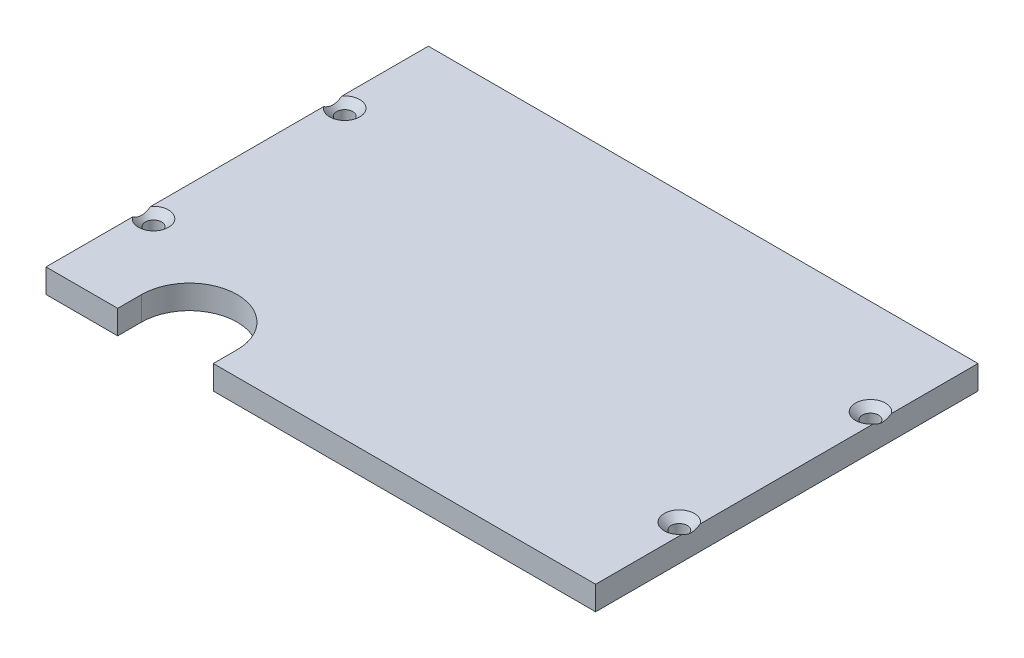
SolidWorks part; units mm, degrees
material "Acrylic"
ref_plane "Front" through (0, 0, 0) normal (0, 0, 1) x (1, 0, 0)
ref_plane "Top" through (0, 0, 0) normal (0, 1, 0) x (1, 0, 0)
ref_plane "Right" through (0, 0, 0) normal (1, 0, 0) x (0, 0, -1)
sketch "Sketch1" plane through (0, 0, 0) normal (0, 1, 0) x (1, 0, 0)
  line L0 (15, 5) -> (15, 0)
  line L1 (0, 0) -> (15, 0)
  line L2 (0, 0) -> (0, 80)
  line L3 (0, 80) -> (115, 80)
  line L4 (115, 0) -> (115, 80)
  line L5 (35, 5) -> (35, 0)
  line L6 (35, 0) -> (115, 0)
  arc A0 (35, 5) -> (15, 5) centre (25, 5) ccw
  dimension "D4" = 10
  dimension "D1" = 80
  dimension "D2" = 115
  dimension "D3" = 5
  dimension "D5" = 25
extrude "Boss-Extrude1" add sketch "Sketch1" against normal blind 5
hole_wizard "CSK for M3 Flat Countersunk Head Screw1" positions "Sketch2" profile "Sketch3" countersink size "M3" standard "JIS" end condition through all
sketch "Sketch2" plane through (0, 0, 0) normal (0, 1, 0) x (1, 0, 0)
  line L0 (0, 80) -> (0, 0) construction
  line L1 (0, 0) -> (15, 0) construction
  point P0 (2.5, 60)
  point P2 (2.5, 20)
  point P4 (112.5, 60)
  point P6 (112.5, 20)
  dimension "D1" = 2.5
  dimension "D2" = 112.5
  dimension "D3" = 60
  dimension "D4" = 20
sketch "Sketch3" plane through (2.5, 0, -60) normal (1, 0, 0) x (0, 0, 1)
  line L0 (0, 0) -> (0, 5)
  line L1 (0, 5) -> (1.7, 5)
  line L2 (1.7, 5) -> (1.7, 1.45)
  line L3 (1.7, 1.45) -> (3.15, 0)
  line L5 (3.15, 0) -> (0, 0)
  line L6 (-1.7, 1.45) -> (-3.15, 0) construction
  line L11 (0, -6.35) -> (0, 107.95) construction
  dimension "Thru Hole Dia." = 3.4
  dimension "Thru Hole Depth" = 5
  dimension "Near C'Sink Dia." = 6.3
  dimension "Near C'Sink Angle" = 90
